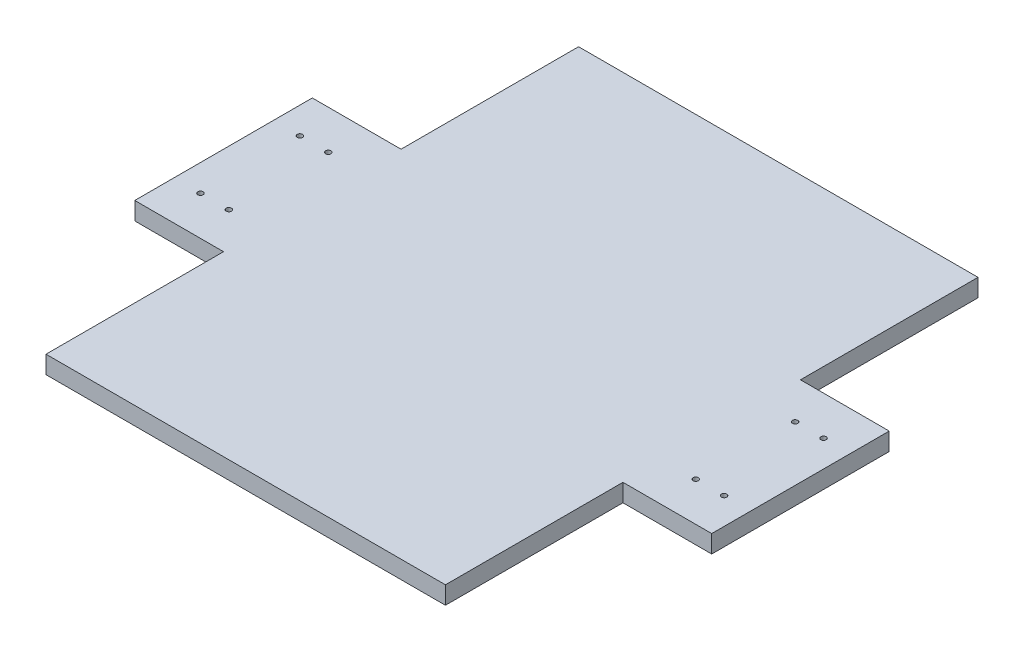
SolidWorks part; units mm, degrees
ref_plane "Front Plane" through (0, 0, 0) normal (0, 0, 1) x (1, 0, 0)
ref_plane "Top Plane" through (0, 0, 0) normal (0, 1, 0) x (1, 0, 0)
ref_plane "Right Plane" through (0, 0, 0) normal (1, 0, 0) x (0, 0, -1)
sketch "Sketch1" plane through (0, 0, 0) normal (0, 1, 0) x (1, 0, 0)
  line L0 (0, -300) -> (0, 300) construction
  line L1 (-225, -300) -> (225, -300)
  line L2 (-325, -100) -> (-325, 100)
  line L3 (-225, 300) -> (225, 300)
  line L4 (325, -100) -> (325, 100)
  line L9 (325, -100) -> (225, -100)
  line L10 (225, -300) -> (225, -100)
  line L11 (325, 0) -> (-325, 0) construction
  line L12 (-325, -100) -> (-225, -100)
  line L13 (-225, -300) -> (-225, -100)
  line L16 (325, 100) -> (225, 100)
  line L17 (225, 300) -> (225, 100)
  line L21 (-225, 300) -> (-225, 100)
  line L22 (-325, 100) -> (-225, 100)
  point P0 (0, 0)
  dimension "D3" = 100
  dimension "D4" = 200
extrude "Boss-Extrude1" add sketch "Sketch1" along normal blind 20
sketch "Sketch2" plane through (0, 20, 0) normal (0, 1, 0) x (1, 0, 0)
  line L0 (-325, 100) -> (-325, -100) construction
  circle A0 centre (-295, -56) radius 3
  circle A1 centre (-263, -56) radius 3
  circle A2 centre (-263, 56) radius 3
  circle A3 centre (-295, 56) radius 3
  point P8 (0, 0)
  point P9 (0, 0)
  point P10 (0, 0)
  point P11 (0, 0)
  point P12 (0, 0)
  point P13 (0, 0)
  point P16 (0, 0)
  point P17 (0, 0)
  point P18 (0, 0)
  point P19 (-295, -54.2235)
  point P20 (0, 0)
  point P21 (0, 0)
  dimension "D1" = 6
  dimension "D2" = 112
  dimension "D3" = 32
  dimension "D4" = 30
  dimension "D5" = 56
extrude "Cut-Extrude1" cut sketch "Sketch2" against normal up to next
mirror "Mirror1" about plane through (0, 0, 0) normal (1, 0, 0) of "Cut-Extrude1"
